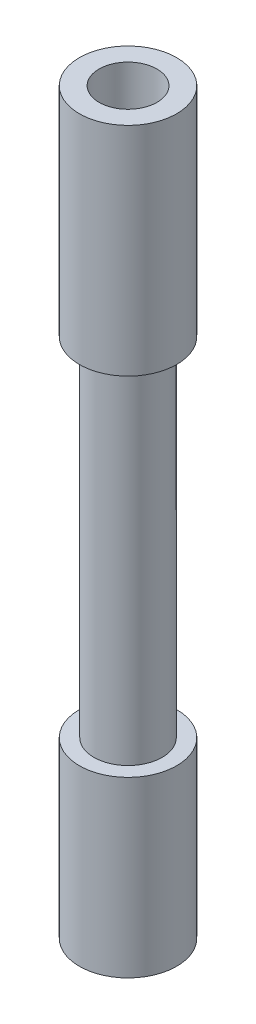
SolidWorks part; units mm, degrees
ref_plane "Front Plane" through (0, 0, 0) normal (0, 0, 1) x (1, 0, 0)
ref_plane "Top Plane" through (0, 0, 0) normal (0, 1, 0) x (1, 0, 0)
ref_plane "Right Plane" through (0, 0, 0) normal (1, 0, 0) x (0, 0, -1)
sketch "Sketch1" plane through (0, 0, 0) normal (0, 0, 1) x (1, 0, 0)
  line L0 (2, 0) -> (3.175, 0)
  line L1 (3.175, 0) -> (3.175, 9.525)
  line L2 (3.175, 9.525) -> (5.334, 9.525)
  line L3 (5.334, 9.525) -> (5.334, -9.525)
  line L4 (5.334, -9.525) -> (2, -9.525)
  line L5 (2, -9.525) -> (2, 0)
  line L6 (0, 0) -> (0, 10.8943) construction
  dimension "D1" = 19.05
  dimension "D2" = 5.334
  dimension "D3" = 3.175
  dimension "D4" = 2
  dimension "D5" = 9.525
  dimension "D6" = 9.525
revolve "Revolve1" add sketch "Sketch1" angle 360 about L6
sketch "Sketch2" plane through (0, -9.525, 0) normal (0, -1, 0) x (1, 0, 0)
  circle A0 centre (0, 0) radius 2 construction
  circle A1 centre (0, 0) radius 5.334
  circle A2 centre (0, 0) radius 5.334
  circle A3 centre (0, 0) radius 2
  dimension "D1" = 0
extrude "Boss-Extrude1" add sketch "Sketch2" along normal blind 61.9125
sketch "Sketch3" plane through (0, -71.4375, 0) normal (0, -1, 0) x (1, 0, 0)
  circle A0 centre (0, 0) radius 5.334
  circle A1 centre (0, 0) radius 3.7465
  circle A2 centre (0, 0) radius 5.334 construction
  dimension "D1" = 1.5875
extrude "Cut-Extrude1" cut sketch "Sketch3" against normal blind 38.1 from offset 19.05
